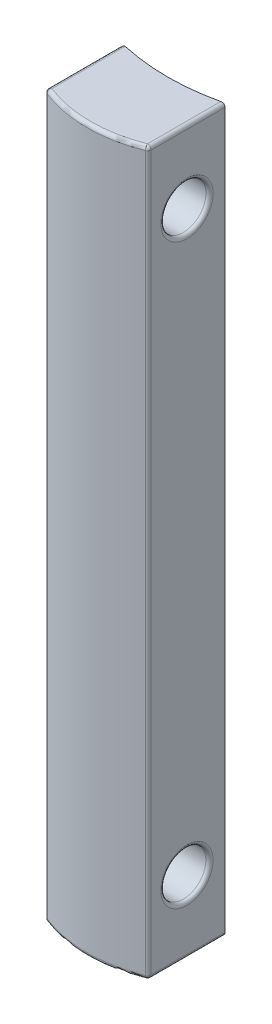
SolidWorks part; units mm, degrees
material "ABS"
ref_plane "Front Plane" through (0, 0, 0) normal (0, 0, 1) x (1, 0, 0)
ref_plane "Top Plane" through (0, 0, 0) normal (0, 1, 0) x (1, 0, 0)
ref_plane "Right Plane" through (0, 0, 0) normal (1, 0, 0) x (0, 0, -1)
sketch "Sketch1" plane through (0, 0, 0) normal (0, 1, 0) x (1, 0, 0)
  line L0 (10.0965, -6.1148) -> (18.0975, -43.3652) construction
  line L2 (-18.0975, -16.4482) -> (-18.0975, -43.3652)
  line L4 (18.0975, -16.4482) -> (18.0975, -43.3652)
  line L6 (-18.0975, -43.3652) -> (-3.4239, -8.2042) construction
  arc A0 (-18.0975, -43.3652) -> (18.0975, -43.3652) centre (0, 0) ccw
  arc A3 (-18.0975, -16.4482) -> (18.0975, -16.4482) centre (0, 57.5716) ccw
  point P8 (0, -46.99)
  point P10 (0, -18.6284)
  point P11 (0, 0)
  dimension "D1" = 93.98
  dimension "D2" = 76.2
  dimension "D3" = 36.195
extrude "Boss-Extrude1" add sketch "Sketch1" along normal blind 254
sketch "Sketch2" plane through (18.0975, 0, 0) normal (1, 0, 0) x (0, 0, -1)
  line L0 (-29.9067, 228.6) -> (-29.9067, 25.4) construction
  line L1 (-16.4482, 254) -> (-16.4482, 0) construction
  line L2 (-43.3652, 0) -> (-16.4482, 0) construction
  circle A0 centre (-29.9067, 228.6) radius 7.9375
  circle A1 centre (-29.9067, 25.4) radius 7.9375
  point P4 (-16.4482, 127)
  point P5 (-29.9067, 127)
  point P8 (-29.9067, 0)
  dimension "D1" = 15.875
  dimension "D2" = 203.2
extrude "Cut-Extrude1" cut sketch "Sketch2" against normal through all
fillet "Fillet1" radius 1.27 13 edges at (18.0975, 228.6, 21.9692) (-18.0975, 228.6, 21.9692) (18.0975, 25.4, 21.9692) (-18.0975, 25.4, 21.9692) (-18.0975, 0, 29.9067) (-18.0975, 127, 16.4482) (18.0975, 0, 29.9067) (0, 0, 46.99) (-18.0975, 254, 29.9067) (18.0975, 254, 29.9067) (-18.0975, 127, 43.3652) (18.0975, 127, 43.3652) (0, 254, 46.99)
